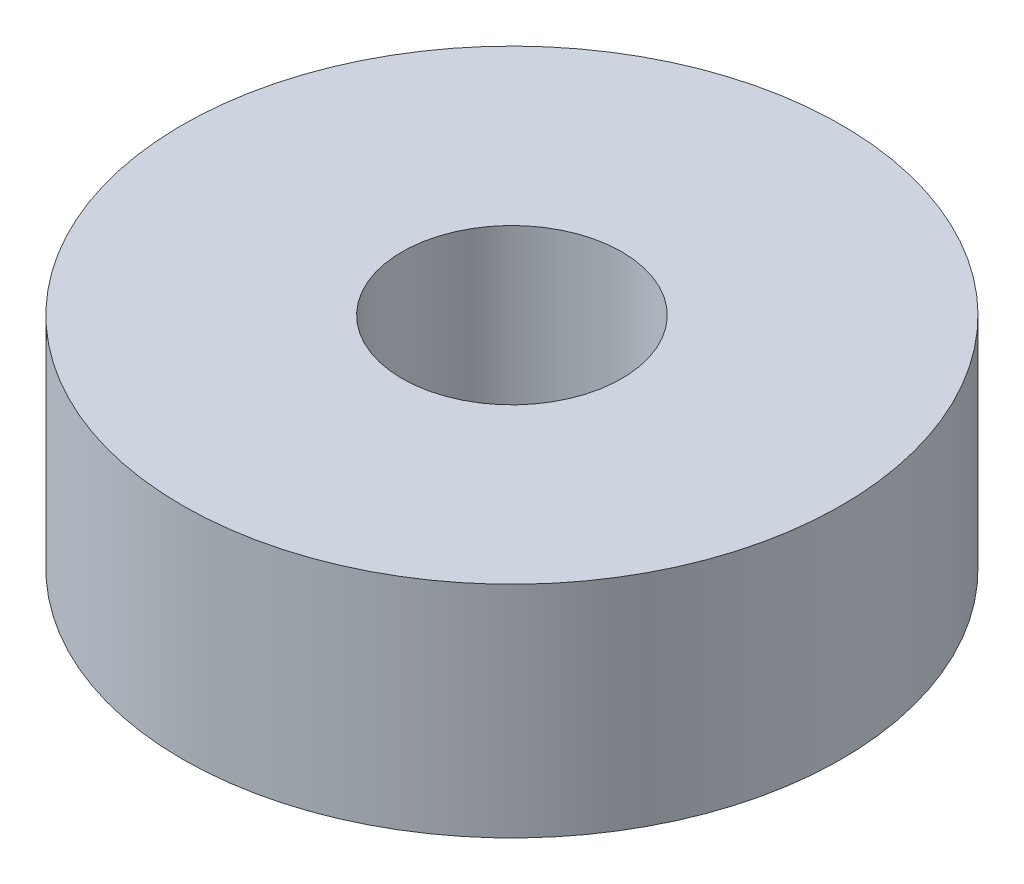
SolidWorks part; units mm, degrees
ref_plane "Front Plane" through (0, 0, 0) normal (0, 0, 1) x (1, 0, 0)
ref_plane "Top Plane" through (0, 0, 0) normal (0, 1, 0) x (1, 0, 0)
ref_plane "Right Plane" through (0, 0, 0) normal (1, 0, 0) x (0, 0, -1)
sketch "Sketch1" plane through (0, 0, 0) normal (0, 1, 0) x (1, 0, 0)
  circle A0 centre (0, 0) radius 5
  circle A1 centre (0, 0) radius 15
  dimension "D1" = 10
  dimension "D2" = 30
extrude "Boss-Extrude1" add sketch "Sketch1" along normal blind 10
